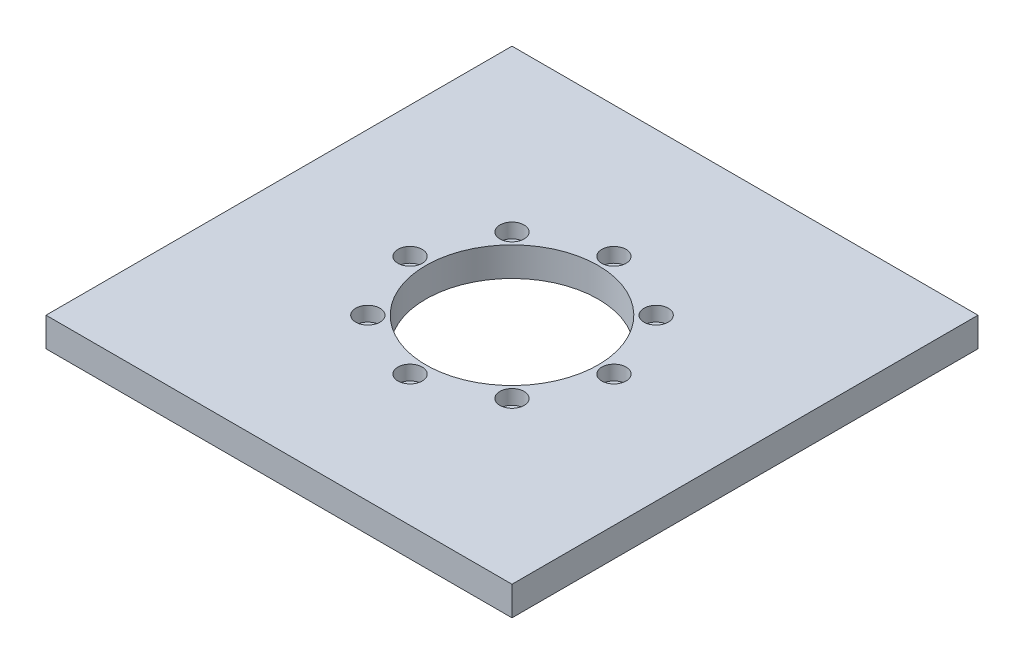
SolidWorks part; units mm, degrees
material "6061-T6 (SS)"
ref_plane "Front Plane" through (0, 0, 0) normal (0, 0, 1) x (1, 0, 0)
ref_plane "Top Plane" through (0, 0, 0) normal (0, 1, 0) x (1, 0, 0)
ref_plane "Right Plane" through (0, 0, 0) normal (1, 0, 0) x (0, 0, -1)
sketch "Sketch1" plane through (0, 0, 0) normal (0, 1, 0) x (1, 0, 0)
  line L1 (152.4, -152.4) -> (-152.4, -152.4)
  line L2 (152.4, -152.4) -> (152.4, 152.4)
  line L3 (152.4, 152.4) -> (-152.4, 152.4)
  line L4 (-152.4, -152.4) -> (-152.4, 152.4)
  line L5 (152.4, -152.4) -> (-152.4, 152.4) construction
  line L6 (152.4, 152.4) -> (-152.4, -152.4) construction
  circle A0 centre (0, 0) radius 56.3562
  point P0 (0, 0)
  dimension "D3" = 112.7125
  dimension "D1" = 304.8
  dimension "D2" = 304.8
extrude "Boss-Extrude1" add sketch "Sketch1" along normal blind 19.05
hole_wizard "CBORE for 3/8 Socket Head Cap Screw1" positions "Sketch2" profile "Sketch3" counterbore size "3/8" standard "ANSI Inch" end condition through all
sketch "Sketch2" plane through (0, 19.05, 0) normal (0, 1, 0) x (1, 0, 0)
  line L1 (66.675, 0) -> (47.1463, 47.1463)
  line L2 (47.1463, 47.1463) -> (0, 66.675)
  line L3 (0, 66.675) -> (-47.1463, 47.1463)
  line L4 (-47.1463, 47.1463) -> (-66.675, 0)
  line L5 (-66.675, 0) -> (-47.1463, -47.1463)
  line L6 (-47.1463, -47.1463) -> (0, -66.675)
  line L7 (0, -66.675) -> (47.1463, -47.1463)
  line L8 (47.1463, -47.1463) -> (66.675, 0)
  line L9 (0, 0) -> (66.675, 0) construction
  circle A0 centre (0, 0) radius 66.675 construction
  point P3 (66.675, 0)
  point P4 (47.1463, 47.1463)
  point P5 (0, 66.675)
  point P6 (-47.1463, 47.1463)
  point P7 (-66.675, 0)
  point P8 (-47.1463, -47.1463)
  point P9 (0, -66.675)
  point P10 (47.1463, -47.1463)
  dimension "D1" = 133.35
sketch "Sketch3" plane through (47.1463, 19.05, 47.1463) normal (1, 0, 0) x (0, 0, 1)
  line L0 (0, 0) -> (0, 19.05)
  line L1 (0, 19.05) -> (4.9022, 19.05)
  line L3 (4.9022, 19.05) -> (4.9022, 9.525)
  line L4 (4.9022, 9.525) -> (7.9375, 9.525)
  line L5 (7.9375, 9.525) -> (7.9375, 0)
  line L7 (7.9375, 0) -> (0, 0)
  line L11 (0, -6.35) -> (0, 107.95) construction
  dimension "Thru Hole Dia." = 9.8044
  dimension "Thru Hole Depth" = 19.05
  dimension "C'Bore Dia." = 15.875
  dimension "C'Bore Depth" = 9.525
